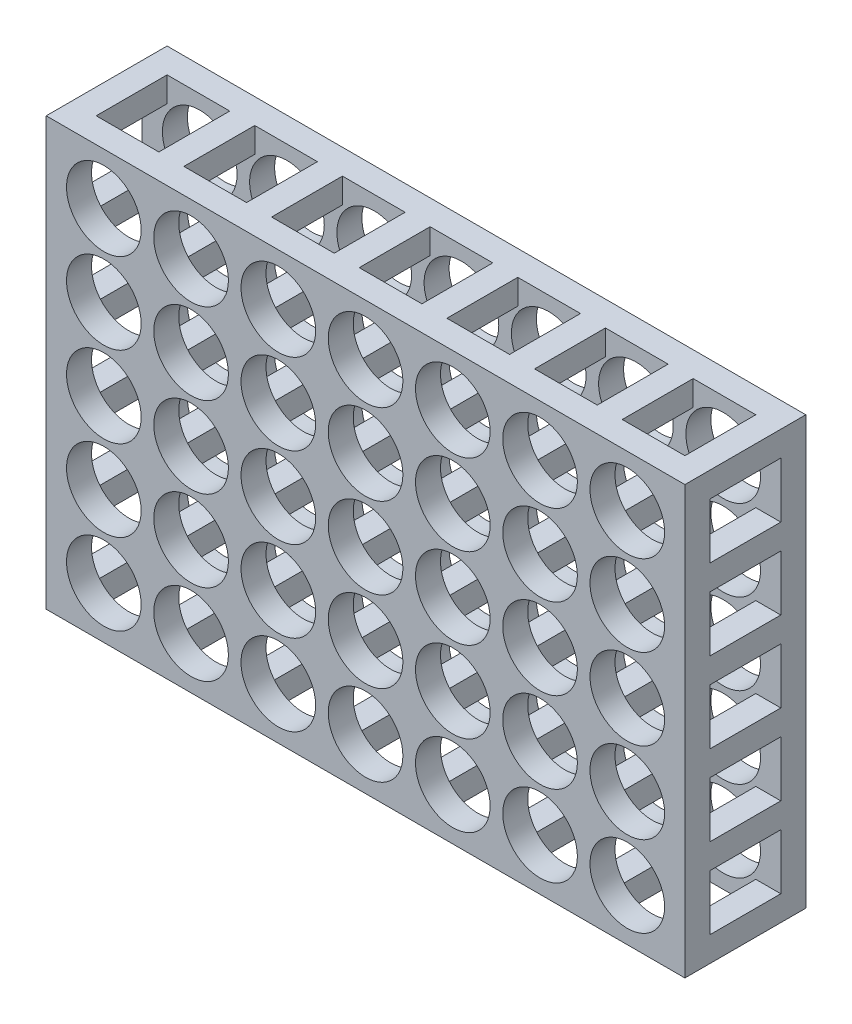
SolidWorks part; units mm, degrees
ref_plane "Front Plane" through (0, 0, 0) normal (0, 0, 1) x (1, 0, 0)
ref_plane "Top Plane" through (0, 0, 0) normal (0, 1, 0) x (1, 0, 0)
ref_plane "Right Plane" through (0, 0, 0) normal (1, 0, 0) x (0, 0, -1)
sketch "Sketch1" plane through (0, 0, 0) normal (0, 0, 1) x (1, 0, 0)
  line L1 (-54.6738, 25.2702) -> (73.0862, 25.2702)
  line L2 (-54.6738, 25.2702) -> (-54.6738, -60.2098)
  line L3 (-54.6738, -60.2098) -> (73.0862, -60.2098)
  line L4 (73.0862, 25.2702) -> (73.0862, -60.2098)
  dimension "D1" = 127.76
  dimension "D2" = 85.48
extrude "Boss-Extrude1" add sketch "Sketch1" along normal blind 5
sketch "Sketch2" plane through (0, 0, 5) normal (0, 0, 1) x (1, 0, 0)
  line L0 (-54.6738, 25.2702) -> (-54.6738, -60.2098) construction
  line L1 (73.0862, 25.2702) -> (-54.6738, 25.2702) construction
  circle A0 centre (-43.1475, 14.9735) radius 7.465
  dimension "D1" = 14.93
  dimension "D2" = 11.5262
  dimension "D3" = 10.2967
extrude "Cut-Extrude1" cut sketch "Sketch2" against normal through all
sketch "Sketch3" plane through (0, 0, 5) normal (0, 0, 1) x (1, 0, 0)
  line L1 (-54.6738, 25.2702) -> (-49.6738, 25.2702)
  line L2 (-54.6738, 25.2702) -> (-54.6738, 20.2702)
  line L3 (-54.6738, 20.2702) -> (-49.6738, 20.2702)
  line L4 (-49.6738, 25.2702) -> (-49.6738, 20.2702)
  dimension "D1" = 5
  dimension "D2" = 5
extrude "Boss-Extrude2" add sketch "Sketch3" along normal blind 7.09
pattern_linear "LPattern2" count 7 spacing 17.4512 along (1, 0, 0) count 5 spacing 16.2217 along (0, -1, 0) of "Cut-Extrude1"
sketch "Sketch4" plane through (0, 0, 5) normal (0, 0, 1) x (1, 0, 0)
  line L2 (-31.9219, 4.5485) -> (-36.9219, 4.5485)
  line L3 (-31.9219, 4.5485) -> (-31.9219, 9.5485)
  line L4 (-31.9219, 9.5485) -> (-36.9219, 9.5485)
  line L5 (-36.9219, 4.5485) -> (-36.9219, 9.5485)
  line L6 (-31.9219, 4.5485) -> (-36.9219, 9.5485) construction
  line L7 (-31.9219, 9.5485) -> (-36.9219, 4.5485) construction
  circle A0 centre (-43.1475, 14.9735) radius 7.465 construction
  circle A3 centre (-25.6963, 14.9735) radius 7.465 construction
  point P2 (-34.4219, 7.0485)
  dimension "D2" = 5
  dimension "D1" = 5
  dimension "D4" = 7.925
  dimension "D3" = 8.7256
pattern_linear "LPattern5" count 8 spacing 17.5371 along (1, 0, 0) count 6 spacing 16.096 along (0, -1, 0) of "Boss-Extrude2"
ref_plane "Plane1" through (0, 0, 12.09) normal (0, 0, -1) x (-1, 0, 0)
mirror "Mirror9" about plane through (0, 0, 12.09) normal (0, 0, -1) of bodies 112 111
equation "\"platewidth\"=127.76"
equation "\"D1@Sketch1\"=\"platewidth\""
equation "\"plateheight\"=85.48"
equation "\"D2@Sketch1\"=\"plateheight\""
equation "\"od\"= \"od_meas\" + \"od_offset\""
equation "\"height\"= \"height_overall\" - \"neck_offset\""
equation "\"minspacing\"= 4'min padding between vials"
equation "\"nx\"= int ( ( \"platewidth\" - \"minspacing\" ) / ( \"od\" + \"minspacing\" ) )'force spacing on left and right ends"
equation "\"ny\"= int ( ( \"plateheight\" - \"minspacing\" ) / ( \"od\" + \"minspacing\" ) )"
equation "\"xspacing\" = ( \"platewidth\" - ( \"nx\" * \"od\" ) ) / ( \"nx\" + 1 )"
equation "\"yspacing\" = ( \"plateheight\" - ( \"ny\" * \"od\" ) ) / ( \"ny\" + 1 )"
equation "\"od_offset\"= 0.3'extra width to print vial holes"
equation "\"od_meas\" = 11.55'measured vial outer dimension (mm)"
equation "\"neck_offset\" = 8'distance from top of threads to wide point of vial"
equation "\"height_overall\"= 32.18'overall height of vial"
equation "\"D3@Sketch2\"=\"yspacing\" + (\"od\"/2)"
equation "\"D2@Sketch2\"= \"xspacing\" + \"od\"/2"
equation "\"D1@Boss-Extrude2\"= (\"height\"/2) - 5"
equation "\"D1@LPattern2\"= \"nx\""
equation "\"D3@LPattern2\"=\"od\" + \"xspacing\""
equation "\"D2@LPattern2\"= \"ny\""
equation "\"D4@LPattern2\"=\"od\" + \"yspacing\""
equation "\"D3@LPattern5\"=(\"platewidth\"-5)/(\"nx\")"
equation "\"D1@LPattern5\"=\"nx\" + 1"
equation "\"D4@LPattern5\"=(\"plateheight\"-5)/\"ny\""
equation "\"xpitch\" = \"od\" + \"xspacing\"'center to center distance of wells"
equation "\"D4@Sketch4\"= (\"minspacing\"+\"od\")/2"
equation "\"D3@Sketch4\"= \"xpitch\"/2"
equation "\"D2@LPattern5\"= \"ny\" + 1"
equation "\"ypitch\"= \"od\" + \"yspacing\""
